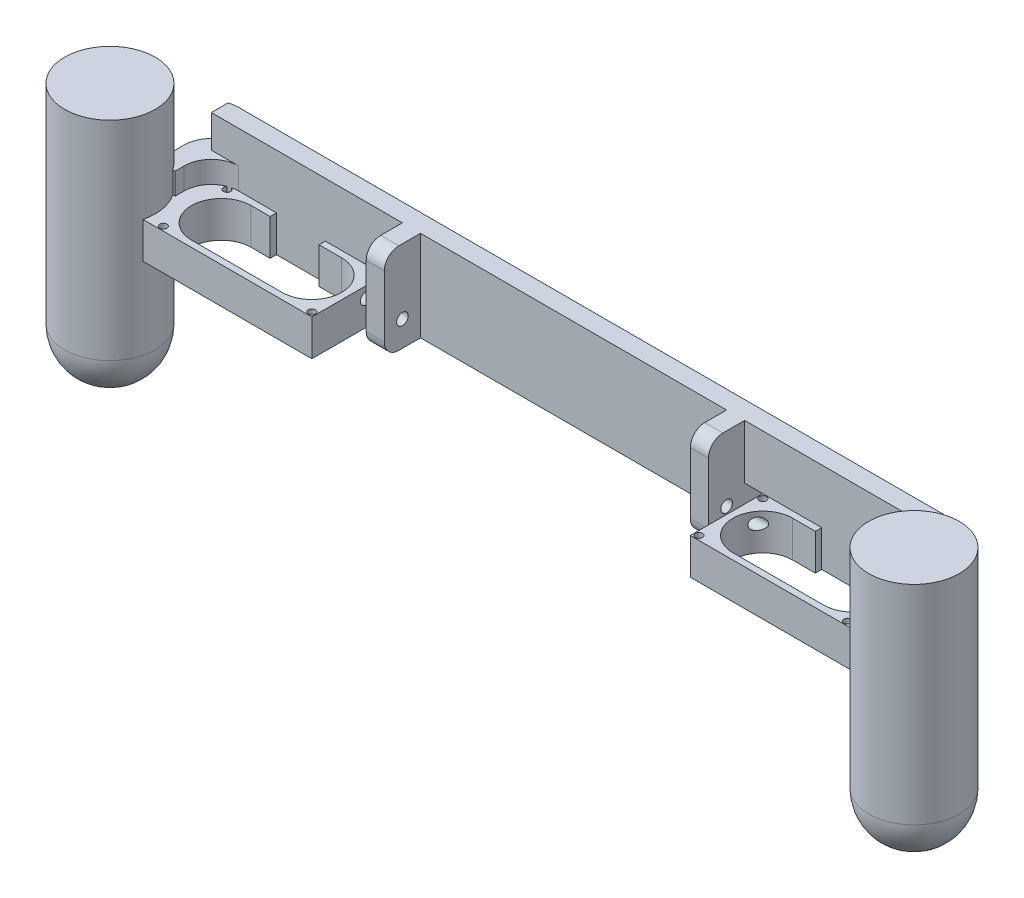
SolidWorks part; units mm, degrees
ref_plane "前视基准面" through (0, 0, 0) normal (0, 0, 1) x (1, 0, 0)
ref_plane "上视基准面" through (0, 0, 0) normal (0, 1, 0) x (1, 0, 0)
ref_plane "右视基准面" through (0, 0, 0) normal (1, 0, 0) x (0, 0, -1)
sketch "草图1" plane through (0, 0, 0) normal (0, 0, 1) x (1, 0, 0)
  line L0 (-45.482, 8.1989) -> (49.018, 8.1989)
  line L1 (-98.232, 33.1989) -> (101.768, 33.1989)
  line L2 (-98.232, 33.1989) -> (-98.232, 8.1989)
  line L3 (-98.232, 8.1989) -> (-50.482, 8.1989)
  line L4 (101.768, 33.1989) -> (101.768, 8.1989)
  line L5 (54.018, 8.1989) -> (101.768, 8.1989)
  line L6 (-50.482, 8.1989) -> (-50.482, 18.1989)
  line L7 (-50.482, 18.1989) -> (-45.482, 18.1989)
  line L8 (-45.482, 8.1989) -> (-45.482, 18.1989)
  line L10 (49.018, 8.1989) -> (49.018, 18.1989)
  line L11 (49.018, 18.1989) -> (54.018, 18.1989)
  line L12 (54.018, 8.1989) -> (54.018, 18.1989)
  dimension "D1" = 200
  dimension "D2" = 25
  dimension "D3" = 47.75
  dimension "D4" = 5
  dimension "D5" = 10
  dimension "D6" = 94.5
  dimension "D7" = 5
  dimension "D8" = 10
extrude "凸台-拉伸1" add sketch "草图1" along normal blind 5
sketch "草图2" plane through (0, 0, 5) normal (0, 0, 1) x (1, 0, 0)
  line L0 (101.768, 33.1989) -> (-98.232, 33.1989) construction
  line L1 (-45.482, 8.1989) -> (-40.482, 8.1989)
  line L2 (-45.482, 8.1989) -> (-45.482, 33.1989)
  line L3 (-45.482, 33.1989) -> (-40.482, 33.1989)
  line L4 (-40.482, 8.1989) -> (-40.482, 33.1989)
  line L6 (49.018, 8.1989) -> (44.018, 8.1989)
  line L7 (49.018, 8.1989) -> (49.018, 33.1989)
  line L8 (49.018, 33.1989) -> (44.018, 33.1989)
  line L9 (44.018, 8.1989) -> (44.018, 33.1989)
  dimension "D1" = 5
  dimension "D2" = 5
extrude "凸台-拉伸2" add sketch "草图2" along normal blind 10
sketch "草图3" plane through (49.018, 0, 0) normal (1, 0, 0) x (0, 0, -1)
  line L0 (-15, 8.1989) -> (-15, 33.1989) construction
  line L1 (-15, 8.1989) -> (0, 8.1989) construction
  circle A0 centre (-10, 15.1989) radius 1.5
  dimension "D1" = 3
  dimension "D2" = 5
  dimension "D3" = 7
extrude "切除-拉伸1" cut sketch "草图3" against normal blind 120
fillet "圆角1" radius 4 4 edges at (46.518, 8.1989, 15) (46.518, 33.1989, 15) (-42.982, 8.1989, 15) (-42.982, 33.1989, 15)
sketch "草图4" plane through (0, 0, 0) normal (0, 0, -1) x (-1, 0, 0)
  line L1 (-101.768, 8.1989) -> (-106.768, 8.1989)
  line L2 (-101.768, 8.1989) -> (-101.768, 24.1989)
  line L3 (-101.768, 24.1989) -> (-106.768, 24.1989)
  line L4 (-106.768, 8.1989) -> (-106.768, 24.1989)
  line L5 (98.232, 8.1989) -> (103.232, 8.1989)
  line L6 (98.232, 8.1989) -> (98.232, 24.1989)
  line L7 (98.232, 24.1989) -> (103.232, 24.1989)
  line L8 (103.232, 8.1989) -> (103.232, 24.1989)
  point P10 (-101.768, 16.1989)
  dimension "D1" = 5
  dimension "D2" = 5
extrude "凸台-拉伸3" add sketch "草图4" against normal blind 15
sketch "草图5" plane through (0, 33.1989, 0) normal (0, 1, 0) x (1, 0, 0)
  line L0 (101.768, -15) -> (106.768, -15) construction
  line L1 (-103.232, -15) -> (-98.232, -15) construction
  line L2 (-103.232, -15) -> (-103.232, 0) construction
  line L3 (106.768, -15) -> (106.768, 0) construction
  circle A0 centre (-109.232, -22) radius 12.5
  circle A1 centre (112.768, -22) radius 12.5
  point P6 (104.268, -15)
  point P9 (-100.732, -15)
  point P18 (106.768, -7.5)
  dimension "D1" = 25
  dimension "D2" = 25
  dimension "D3" = 7
  dimension "D4" = 7
  dimension "D5" = 6
  dimension "D6" = 6
fillet "圆角3" radius 7.5 4 edges at (-98.232, 16.1989, 5) (-103.232, 16.1989, 0) (101.768, 16.1989, 5) (106.768, 16.1989, 0)
extrude "凸台-拉伸4" add sketch "草图5" along normal blind 10 and the other way blind 60
fillet "圆角4" radius 12.5 2 edges at (-109.232, -26.8011, 34.5) (112.768, -26.8011, 34.5)
sketch "草图6" plane through (0, 8.1989, 0) normal (0, -1, 0) x (1, 0, 0)
  line L0 (89.018, 6.75) -> (83.8021, 6.75)
  line L1 (54.018, 5) -> (70.296, 5)
  line L2 (54.018, 5) -> (54.018, 25)
  line L3 (54.018, 25) -> (104.018, 25)
  line L4 (104.018, 5) -> (104.018, 25)
  line L5 (89.018, 23.25) -> (64.018, 23.25)
  line L6 (70.296, 6.75) -> (64.018, 6.75)
  line L8 (83.8021, 5) -> (83.8021, 6.75)
  line L9 (83.8021, 5) -> (104.018, 5)
  line L10 (70.296, 5) -> (70.296, 6.75)
  line L11 (1.768, 5) -> (1.768, 14.1517) construction
  line L12 (-40.482, 5) -> (44.018, 5) construction
  line L13 (-66.7601, 5) -> (-66.7601, 6.75)
  line L14 (-80.2661, 5) -> (-80.2661, 6.75)
  line L15 (-66.7601, 6.75) -> (-60.482, 6.75)
  line L16 (-50.482, 5) -> (-66.7601, 5)
  line L17 (-50.482, 5) -> (-50.482, 25)
  line L18 (-85.482, 23.25) -> (-60.482, 23.25)
  line L19 (-50.482, 25) -> (-100.482, 25)
  line L20 (-100.482, 5) -> (-100.482, 25)
  line L21 (-80.2661, 5) -> (-100.482, 5)
  line L22 (-85.482, 6.75) -> (-80.2661, 6.75)
  line L23 (-80.2661, 5) -> (-66.7601, 5)
  arc A0 (89.018, 6.75) -> (89.018, 23.25) centre (89.018, 15) ccw
  arc A1 (64.018, 23.25) -> (64.018, 6.75) centre (64.018, 15) ccw
  arc A2 (-60.482, 23.25) -> (-60.482, 6.75) centre (-60.482, 15) cw
  arc A3 (-85.482, 6.75) -> (-85.482, 23.25) centre (-85.482, 15) cw
  circle A4 centre (55.218, 6.2) radius 1
  circle A5 centre (96.218, 6.2) radius 1
  circle A6 centre (96.218, 23.8) radius 1
  circle A7 centre (55.218, 23.8) radius 1
  circle A8 centre (-92.682, 23.8) radius 1
  circle A9 centre (-92.682, 6.2) radius 1
  circle A10 centre (-51.682, 6.2) radius 1
  circle A11 centre (-51.682, 23.8) radius 1
  point P41 (93.91, 5)
  arc M14 (106.768, 11.0341) -> (102.4118, 15) centre (112.768, 22) cw
  line M15 (102.4118, 15) -> (101.768, 15)
  line M16 (101.768, 15) -> (101.768, 12.5)
  arc M17 (101.768, 12.5) -> (94.268, 5) centre (94.268, 12.5) cw
  line M18 (94.268, 5) -> (54.018, 5)
  dimension "D5" = 16.5
  dimension "D6" = 1.2
  dimension "D11" = 2
  dimension "D12" = 2
  dimension "D15" = 2
  dimension "D16" = 2
  dimension "D1" = 50
  dimension "D2" = 20
  dimension "D3" = 10
  dimension "D4" = 10
  dimension "D7" = 1.2
  dimension "D8" = 25
  dimension "D9" = 1.2
  dimension "D10" = 1.2
  dimension "D13" = 41
  dimension "D14" = 41
  dimension "D17" = 1.2
  dimension "D18" = 1.2
extrude "凸台-拉伸5" add sketch "草图6" against normal blind 10 contours L22 A3 L18 A2 L15 L13 L16 L17 L19 L20 L21 L14 | A1 L5 A0 L0 L8 L4 L3 L2 L10 L6 M18 M17 M16 M15 M14
sketch "草图7" plane through (-40.482, 0, 0) normal (1, 0, 0) x (0, 0, -1)
  circle A0 centre (-10, 15.1989) radius 1.6
  dimension "D1" = 3.2
extrude "切除-拉伸2" cut sketch "草图7" against normal blind 40
sketch "草图8" plane through (44.018, 0, 0) normal (-1, 0, 0) x (0, 0, 1)
  circle A0 centre (10, 15.1989) radius 1.6
  dimension "D1" = 3.2
extrude "切除-拉伸3" cut sketch "草图8" against normal blind 40
